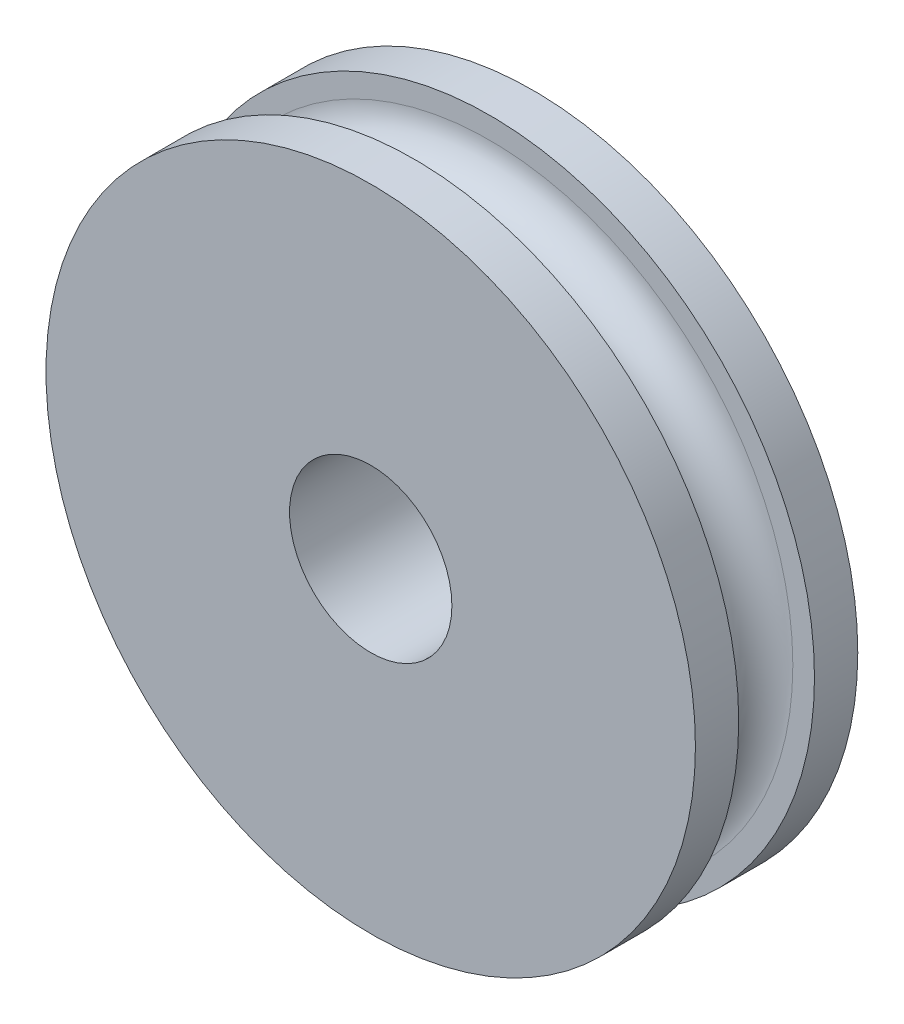
SolidWorks part; units mm, degrees
ref_plane "Front Plane" through (0, 0, 0) normal (0, 0, 1) x (1, 0, 0)
ref_plane "Top Plane" through (0, 0, 0) normal (0, 1, 0) x (1, 0, 0)
ref_plane "Right Plane" through (0, 0, 0) normal (1, 0, 0) x (0, 0, -1)
sketch "Sketch1" plane through (0, 0, 0) normal (1, 0, 0) x (0, 0, -1)
  line L5 (-0.7, 5.6) -> (-0.7, 6)
  line L6 (1.5, 6) -> (0, 0) construction
  line L8 (1.5, 0) -> (1.5, 1.5)
  line L9 (1.5, 1.5) -> (-1.5, 1.5)
  line L10 (-1.5, 0) -> (-1.5, 1.5)
  line L11 (0, 0) -> (-1.5, 1.5) construction
  line L12 (1.5, 1.5) -> (0, 0) construction
  line L13 (-1.5, 0) -> (1.5, 0)
  line L14 (-1.5, 0) -> (-1.5, 6)
  line L15 (-0.7, 6) -> (-1.5, 6)
  line L16 (0, 0) -> (-1.5, 6) construction
  line L17 (1.5, 0) -> (1.5, 6)
  line L18 (0.7, 5.6) -> (0.7, 6)
  line L19 (0.7, 6) -> (1.5, 6)
  arc A0 (0.7, 5.6) -> (-0.7, 5.6) centre (0, 5.6) cw
  point P0 (0, 0)
  point P2 (0, 0)
  point P4 (0, 0)
  point P6 (0, 0)
  dimension "D1" = 0.7
  dimension "D2" = 0.8
  dimension "D3" = 6
  dimension "D4" = 1.5
  dimension "D5" = 0.4
revolve "Revolve1" add sketch "Sketch1" angle 360 about L13
